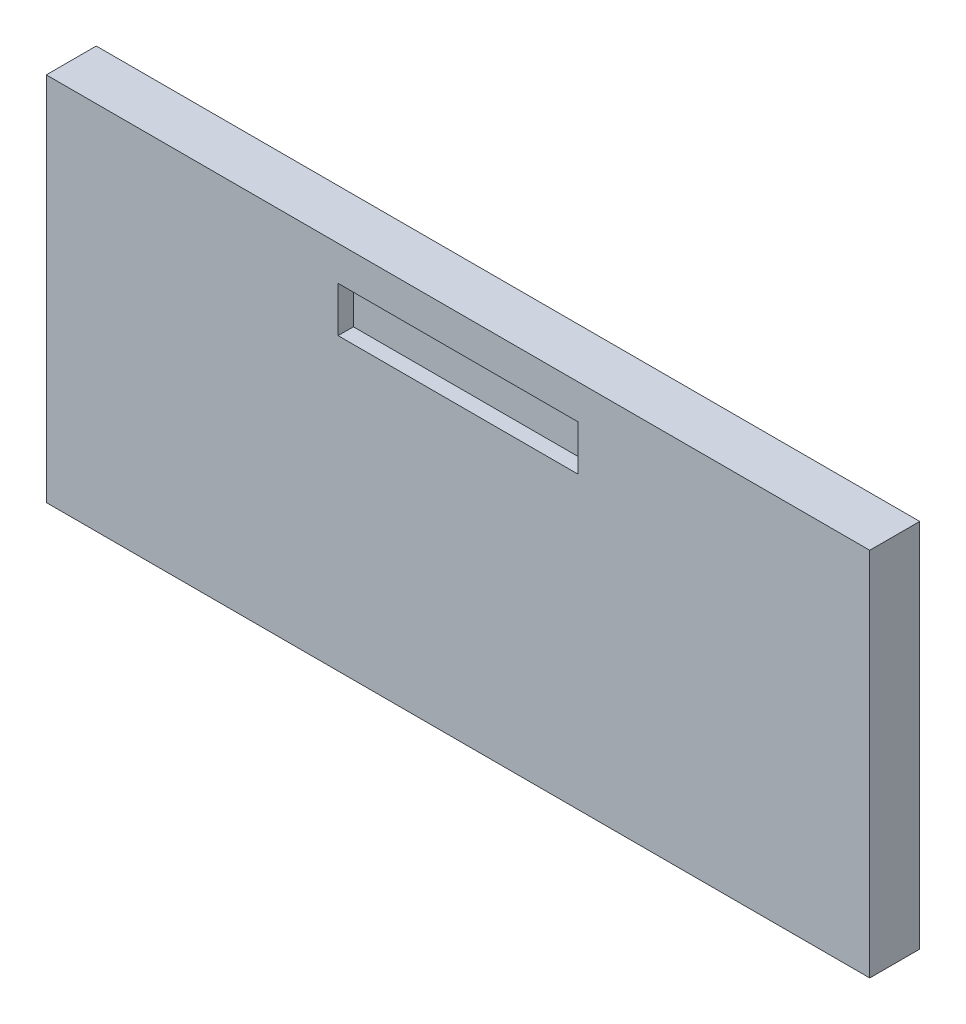
SolidWorks part; units mm, degrees
ref_plane "Front Plane" through (0, 0, 0) normal (0, 0, 1) x (1, 0, 0)
ref_plane "Top Plane" through (0, 0, 0) normal (0, 1, 0) x (1, 0, 0)
ref_plane "Right Plane" through (0, 0, 0) normal (1, 0, 0) x (0, 0, -1)
other "Configuration Table"
sketch "Sketch1" plane through (0, 0, 0) normal (0, 0, 1) x (1, 0, 0)
  line L1 (69, 406) -> (687, 406)
  line L2 (69, 406) -> (69, 684)
  line L3 (69, 684) -> (687, 684)
  line L4 (687, 406) -> (687, 684)
extrude "STORE_klape_kaset_kati_on_pu_1" add sketch "Sketch1" along normal blind 37.5 from offset 1 separate body
sketch "Sketch2" plane through (0, 0, 0) normal (0, 0, 1) x (1, 0, 0)
  line L1 (288, 624) -> (468, 624)
  line L2 (288, 624) -> (288, 658)
  line L3 (288, 658) -> (468, 658)
  line L4 (468, 624) -> (468, 658)
extrude "STORE_klape_kaset_kati_on_pu_2" cut sketch "Sketch2" along normal blind 14 from offset 27
